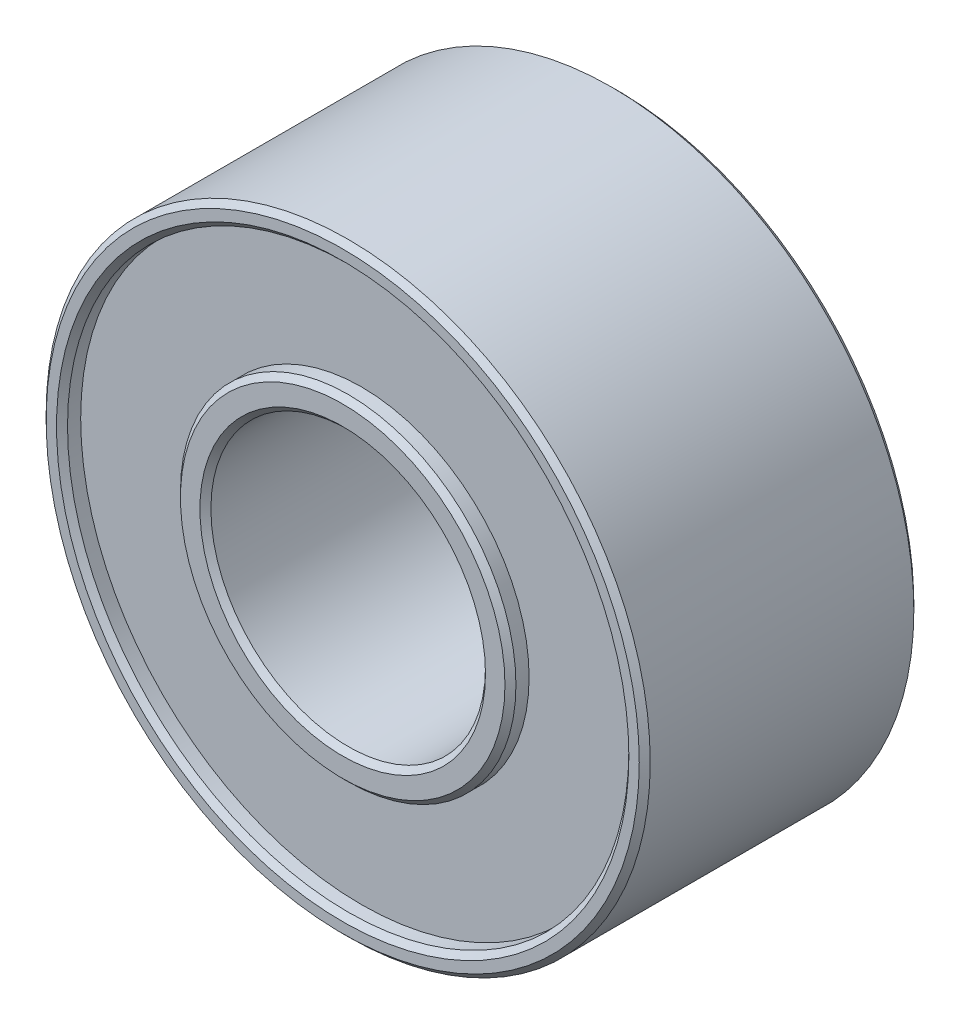
SolidWorks part; units mm, degrees
ref_plane "Front Plane" through (0, 0, 0) normal (0, 0, 1) x (1, 0, 0)
ref_plane "Top Plane" through (0, 0, 0) normal (0, 1, 0) x (1, 0, 0)
ref_plane "Right Plane" through (0, 0, 0) normal (1, 0, 0) x (0, 0, -1)
ref_axis "Axis1" through (0, 0, -19.0783) along (0, 0, 1)
sketch "Sketch1" plane through (0, 0, 0) normal (1, 0, 0) x (0, 0, -1)
  line L0 (19.0783, 0) -> (-24.5011, 0) construction
  line L1 (-2.5, 5.5) -> (2.5, 5.5)
  line L2 (-2.5, 5.5) -> (-2.5, 2.5) construction
  line L3 (-2.5, 2.5) -> (2.5, 2.5)
  line L4 (2.5, 5.5) -> (2.5, 5.1109)
  line L5 (-2.5, 5.5) -> (2.5, 2.5) construction
  line L6 (-2.5, 2.5) -> (2.5, 5.5) construction
  line L7 (0, 4) -> (0, 0) construction
  line L8 (2.5, 3.0545) -> (2.5, 2.5)
  line L9 (2.5, 5.1109) -> (2.1603, 5.1109)
  line L10 (-2.5, 3.0545) -> (-2.5, 2.5)
  line L11 (2.5, 3.0545) -> (2.1603, 3.0545)
  line L12 (2.1603, 5.1109) -> (2.1603, 3.0545)
  line L13 (-2.5, 3.0545) -> (-2.1603, 3.0545)
  line L14 (-2.1603, 5.1109) -> (-2.1603, 3.0545)
  line L15 (-2.5, 5.1109) -> (-2.1603, 5.1109)
  line L16 (-2.5, 5.5) -> (-2.5, 5.1109)
  point P0 (0, 4)
  dimension "D1" = 5.5
  dimension "D2" = 5
  dimension "D3" = 2.5
revolve "Revolve1" add sketch "Sketch1" angle 360 about axis through (0, 0, -19.0783) along (0, 0, 1)
chamfer "Chamfer1" distance 0.1 angle 45 8 edges at (-2.5, 0, -2.5) (-2.5, 0, 2.5) (-5.5, 0, 2.5) (-5.5, 0, -2.5) (-5.1109, 0, -2.5) (-3.0545, 0, -2.5) (-5.1109, 0, 2.5) (-3.0545, 0, 2.5)
